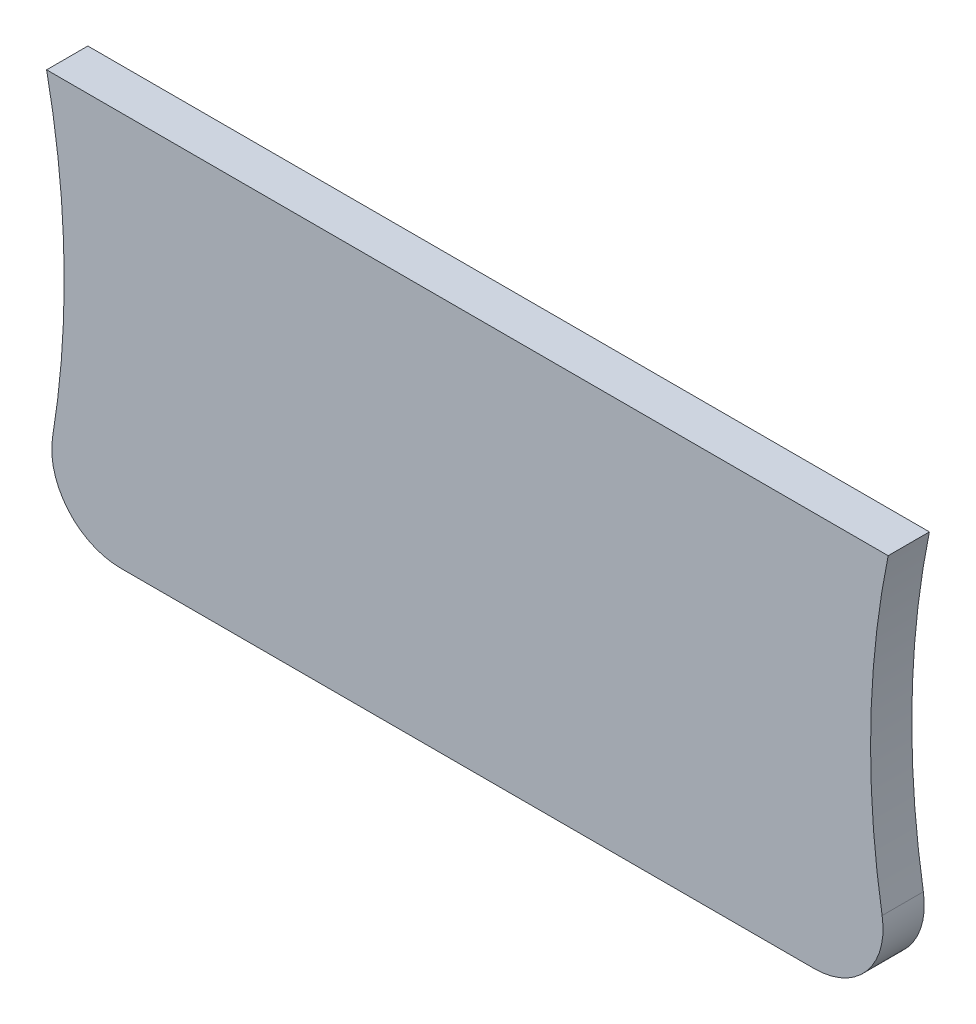
SolidWorks part; units mm, degrees
ref_plane "前视基准面" through (0, 0, 0) normal (0, 0, 1) x (1, 0, 0)
ref_plane "上视基准面" through (0, 0, 0) normal (0, 1, 0) x (1, 0, 0)
ref_plane "右视基准面" through (0, 0, 0) normal (1, 0, 0) x (0, 0, -1)
sketch "草图2" plane through (0, 0, 0) normal (0, 0, 1) x (1, 0, 0)
  line L3 (-96.5036, -60.8816) -> (-46.0101, -60.8816)
  line L4 (-101.8762, -32.168) -> (-40.6375, -32.168)
  arc A0 (-40.6375, -32.168) -> (-41.0769, -55.0673) centre (21.0819, -44.8062) ccw
  arc A3 (-101.4368, -55.0673) -> (-101.8762, -32.168) centre (-163.5956, -44.8062) ccw
  arc A4 (-101.4368, -55.0673) -> (-96.5036, -60.8816) centre (-96.5036, -55.8816) ccw
  arc A5 (-46.0101, -60.8816) -> (-41.0769, -55.0673) centre (-46.0101, -55.8816) ccw
extrude "凸台-拉伸1" add sketch "草图2" along normal blind 3
